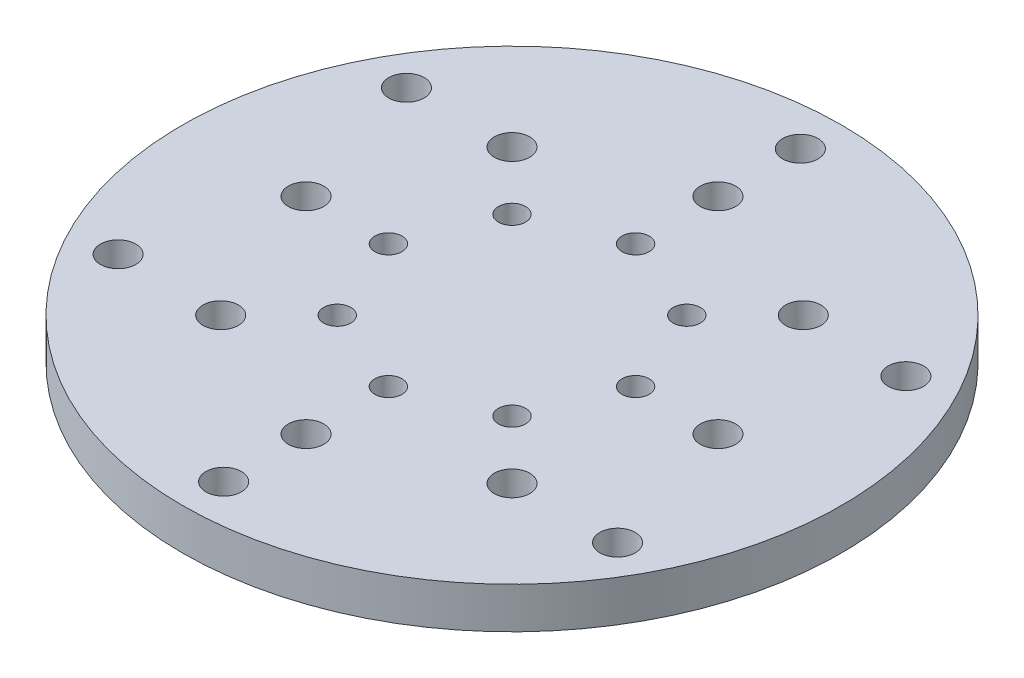
SolidWorks part; units mm, degrees
ref_plane "前视基准面" through (0, 0, 0) normal (0, 0, 1) x (1, 0, 0)
ref_plane "上视基准面" through (0, 0, 0) normal (0, 1, 0) x (1, 0, 0)
ref_plane "右视基准面" through (0, 0, 0) normal (1, 0, 0) x (0, 0, -1)
other "Configuration Table"
sketch "草图1" plane through (0, 0, 0) normal (0, 1, 0) x (1, 0, 0)
  circle A1 centre (0, 0) radius 40
  circle A2 centre (0, 0) radius 35
  circle A3 centre (0, 35) radius 2.15
  circle A4 centre (30.3109, 17.5) radius 2.15
  circle A5 centre (30.3109, -17.5) radius 2.15
  circle A6 centre (0, -35) radius 2.15
  circle A7 centre (-30.3109, -17.5) radius 2.15
  circle A8 centre (-30.3109, 17.5) radius 2.15
  circle A9 centre (0, 0) radius 31
  circle A10 centre (0, 0) radius 25
  circle A19 centre (0, 25) radius 2.15
  circle A20 centre (17.6777, 17.6777) radius 2.15
  circle A21 centre (25, 0) radius 2.15
  circle A22 centre (17.6777, -17.6777) radius 2.15
  circle A23 centre (0, -25) radius 2.15
  circle A24 centre (-17.6777, -17.6777) radius 2.15
  circle A25 centre (-25, 0) radius 2.15
  circle A26 centre (-17.6777, 17.6777) radius 2.15
  circle A27 centre (0, 0) radius 15
  circle A28 centre (0, 15) radius 1.65
  circle A29 centre (10.6066, 10.6066) radius 1.65
  circle A30 centre (15, 0) radius 1.65
  circle A31 centre (10.6066, -10.6066) radius 1.65
  circle A32 centre (0, -15) radius 1.65
  circle A33 centre (-10.6066, -10.6066) radius 1.65
  circle A34 centre (-15, 0) radius 1.65
  circle A35 centre (-10.6066, 10.6066) radius 1.65
  point P19 (0, 0)
  point P38 (3.0178, -1.25)
  point P39 (0, 0)
  point P57 (0, 0)
  dimension "D1" = 80
  dimension "D2" = 70
  dimension "D3" = 4.3
  dimension "D5" = 62
  dimension "D6" = 50
  dimension "D7" = 4.3
  dimension "D9" = 3.3
  dimension "D8" = 30
  dimension "D4" = 6
extrude "凸台-拉伸2" add sketch "草图1" along normal blind 5 contours A1 A8 A2 A3 A4 A5 A6 A7 | A8 A2 A7 A6 A5 A4 A3 A9 | A9 A26 A10 A19 A20 A21 A22 A23 A24 A25 | A26 A10 A25 A24 A23 A22 A21 A20 A19 A35 A27 A28 A29 A30 A31 A32 A33 A34 | A35 A27 A34 A33 A32 A31 A30 A29 A28
